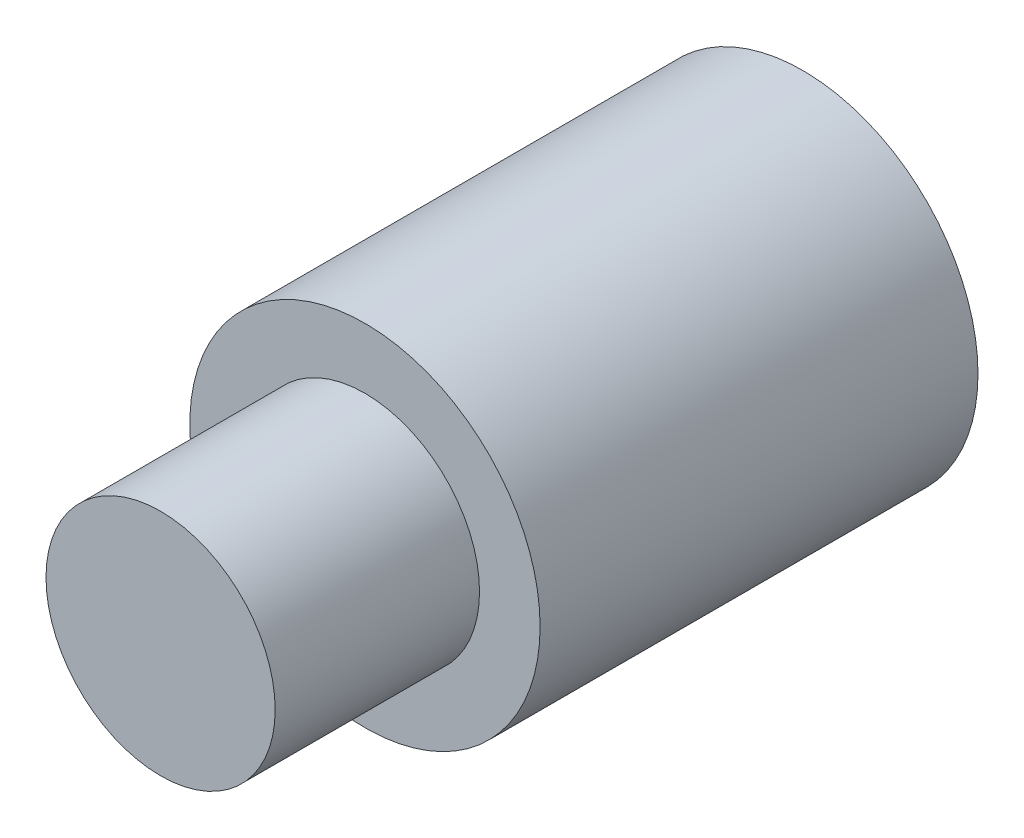
SolidWorks part; units mm, degrees
ref_plane "Ebene vorne" through (0, 0, 0) normal (0, 0, 1) x (1, 0, 0)
ref_plane "Ebene oben" through (0, 0, 0) normal (0, 1, 0) x (1, 0, 0)
ref_plane "Ebene rechts" through (0, 0, 0) normal (1, 0, 0) x (0, 0, -1)
sketch "Skizze1" plane through (0, 0, 0) normal (0, 0, 1) x (1, 0, 0)
  circle A0 centre (0, 0) radius 6
  dimension "D1" = 12
extrude "Aufsatz-Linear austragen1" add sketch "Skizze1" along normal blind 15
sketch "Skizze2" plane through (0, 0, 15) normal (0, 0, 1) x (1, 0, 0)
  circle A0 centre (0, 0) radius 3.925
  dimension "D1" = 7.85
extrude "Aufsatz-Linear austragen2" add sketch "Skizze2" along normal blind 7
